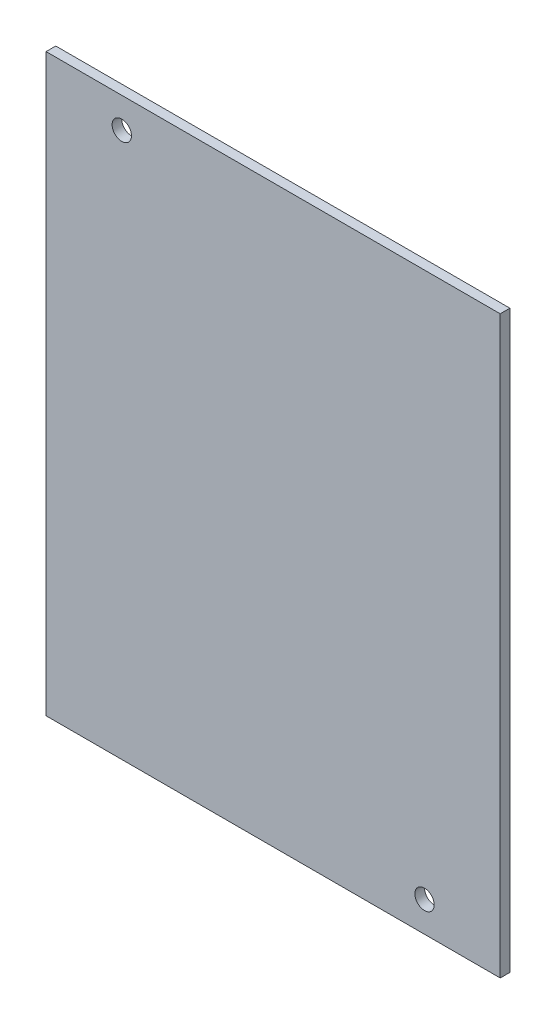
SolidWorks part; units mm, degrees
ref_plane "Front Plane" through (0, 0, 0) normal (0, 0, 1) x (1, 0, 0)
ref_plane "Top Plane" through (0, 0, 0) normal (0, 1, 0) x (1, 0, 0)
ref_plane "Right Plane" through (0, 0, 0) normal (1, 0, 0) x (0, 0, -1)
sketch "Sketch1" plane through (0, 0, 0) normal (0, 0, 1) x (1, 0, 0)
  line L0 (44.2, -10.4) -> (44.2, -95.4) construction
  line L1 (19.2, -10.4) -> (69.2, -10.4) construction
  line L2 (19.2, -10.4) -> (19.2, -95.4) construction
  line L3 (19.2, -95.4) -> (69.2, -95.4) construction
  line L4 (69.2, -10.4) -> (69.2, -95.4) construction
  line L5 (19.2, -52.9) -> (69.2, -52.9) construction
  line L7 (6.7, -100.4) -> (81.7, -100.4)
  line L8 (6.7, -100.4) -> (6.7, -5.4)
  line L9 (6.7, -5.4) -> (81.7, -5.4)
  line L10 (81.7, -100.4) -> (81.7, -5.4)
  line L11 (6.7, -100.4) -> (81.7, -5.4) construction
  line L12 (6.7, -5.4) -> (81.7, -100.4) construction
  circle A0 centre (19.2, -10.4) radius 1.6
  circle A1 centre (69.2, -95.4) radius 1.6
  point P10 (44.2, -52.9)
  dimension "D5" = 3.2
  dimension "D6" = 3.2
  dimension "D1" = 50
  dimension "D2" = 85
  dimension "D3" = 75
  dimension "D4" = 95
extrude "Boss-Extrude1" add sketch "Sketch1" along normal blind 1.6
